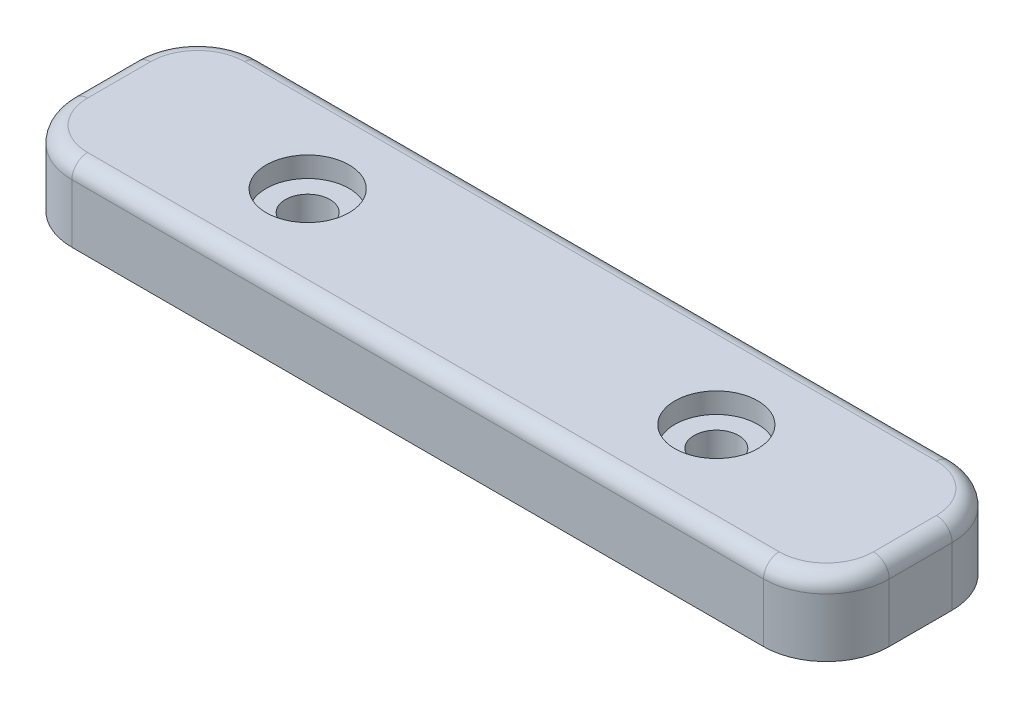
SolidWorks part; units mm, degrees
material "ABS"
ref_plane "Front Plane" through (0, 0, 0) normal (0, 0, 1) x (1, 0, 0)
ref_plane "Top Plane" through (0, 0, 0) normal (0, 1, 0) x (1, 0, 0)
ref_plane "Right Plane" through (0, 0, 0) normal (1, 0, 0) x (0, 0, -1)
sketch "Sketch1" plane through (0, 0, 0) normal (0, 1, 0) x (1, 0, 0)
  line L1 (0, 0) -> (66.04, 0)
  line L2 (0, 0) -> (0, -15.24)
  line L3 (0, -15.24) -> (66.04, -15.24)
  line L4 (66.04, 0) -> (66.04, -15.24)
  dimension "D1" = 66.04
  dimension "D2" = 15.24
extrude "Boss-Extrude1" add sketch "Sketch1" along normal blind 6
sketch "Sketch2" plane through (0, 6, 0) normal (0, 1, 0) x (1, 0, 0)
  line L0 (0, -7.62) -> (66.04, -7.62) construction
  line L1 (0, 0) -> (0, -15.24) construction
  line L2 (66.04, -15.24) -> (66.04, 0) construction
  line L3 (16.51, 0) -> (16.51, -15.24) construction
  line L4 (66.04, 0) -> (0, 0) construction
  line L5 (0, -15.24) -> (66.04, -15.24) construction
  line L6 (49.53, 0) -> (49.53, -15.24) construction
  circle A0 centre (16.51, -7.62) radius 1.6 construction
  circle A1 centre (49.53, -7.62) radius 1.6 construction
  dimension "D3" = 3.2
  dimension "D1" = 16.51
  dimension "D2" = 16.51
hole_wizard "CBORE for M3 SBHCS1" positions "Sketch3" profile "Sketch4" counterbore size "M3" standard "ANSI Metric" end condition through all
sketch "Sketch3" plane through (0, 6, 0) normal (0, 1, 0) x (1, 0, 0)
  point P0 (16.51, -7.62)
  point P3 (49.53, -7.62)
sketch "Sketch4" plane through (16.51, 6, 7.62) normal (1, 0, 0) x (0, 0, 1)
  line L0 (0, 0) -> (0, 6)
  line L1 (0, 6) -> (1.8, 6)
  line L3 (1.8, 6) -> (1.8, 1.65)
  line L4 (1.8, 1.65) -> (3.35, 1.65)
  line L5 (3.35, 1.65) -> (3.35, 0)
  line L7 (3.35, 0) -> (0, 0)
  line L11 (0, -6.35) -> (0, 107.95) construction
  dimension "Thru Hole Dia." = 3.6
  dimension "Thru Hole Depth" = 6
  dimension "C'Bore Dia." = 6.7
  dimension "C'Bore Depth" = 1.65
fillet "Fillet1" radius 5.08 4 edges at (0, 3, 15.24) (0, 3, 0) (66.04, 3, 15.24) (66.04, 3, 0)
fillet "Fillet2" radius 1.27 8 edges at (1.4879, 6, 13.7521) (0, 6, 7.62) (1.4879, 6, 1.4879) (33.02, 6, 0) (64.5521, 6, 1.4879) (66.04, 6, 7.62) (64.5521, 6, 13.7521) (33.02, 6, 15.24)
